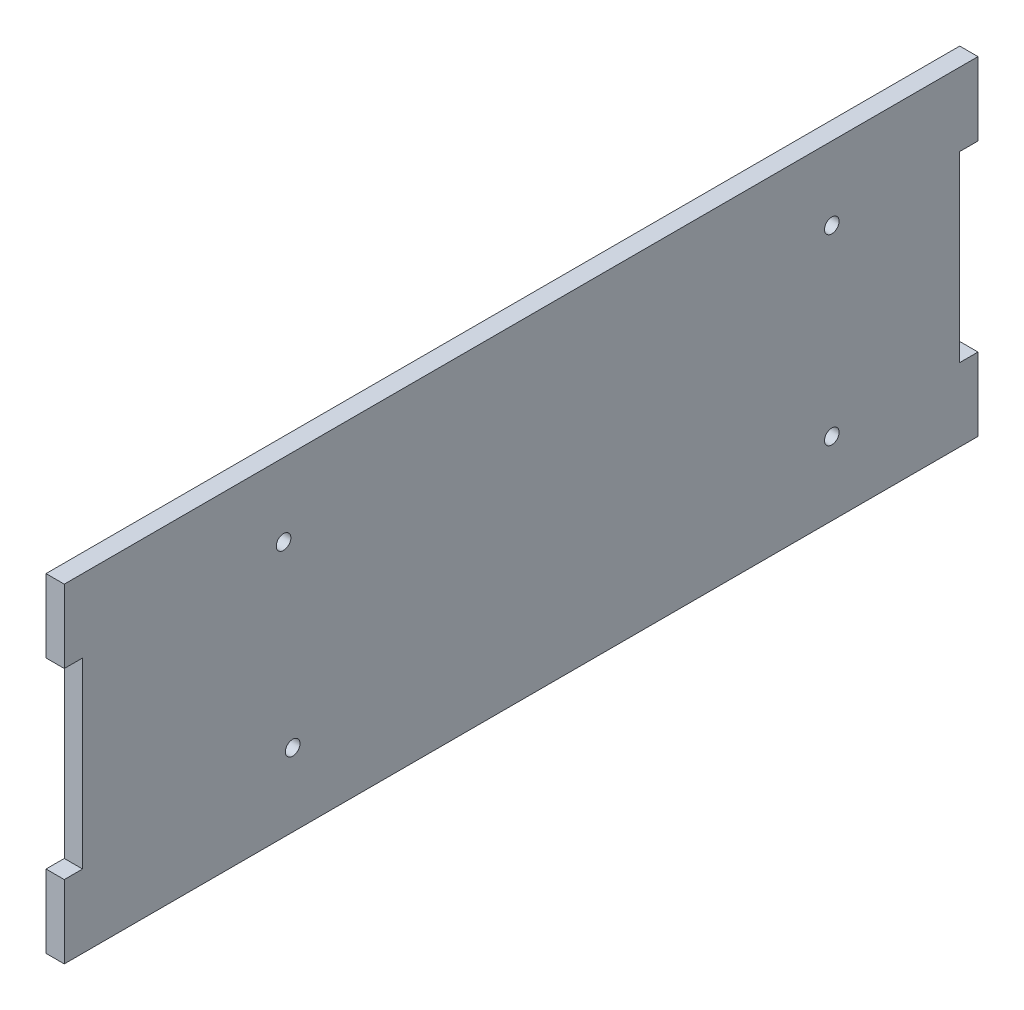
SolidWorks part; units mm, degrees
ref_plane "前视基准面" through (0, 0, 0) normal (0, 0, 1) x (1, 0, 0)
ref_plane "上视基准面" through (0, 0, 0) normal (0, 1, 0) x (1, 0, 0)
ref_plane "右视基准面" through (0, 0, 0) normal (1, 0, 0) x (0, 0, -1)
sketch "草图1" plane through (0, 0, 0) normal (1, 0, 0) x (0, 0, -1)
  line L0 (-276.0239, 70) -> (97.6962, 70) construction
  line L1 (0, 0) -> (-250, 0)
  line L2 (0, 0) -> (0, 20)
  line L3 (0, 90) -> (-250, 90)
  line L4 (-250, 0) -> (-250, 20)
  line L5 (-281.9966, 20) -> (107.0819, 20) construction
  line L6 (-190, 207.5512) -> (-190, -63.3532) construction
  line L7 (-40, 207.5512) -> (-40, -60.3669) construction
  line L8 (-245, 70) -> (-245, 20)
  line L10 (-250, 70) -> (-245, 70)
  line L11 (-250, 20) -> (-245, 20)
  line L12 (0, 20) -> (-5, 20)
  line L13 (0, 70) -> (-5, 70)
  line L14 (-250, 70) -> (-250, 90)
  line L15 (0, 70) -> (0, 90)
  line L16 (-5, 70) -> (-5, 20)
  circle A0 centre (-40, 70) radius 2
  circle A1 centre (-40, 20) radius 2
  circle A2 centre (-187.5, 20) radius 2
  circle A3 centre (-190, 70) radius 2
  dimension "D7" = 5
  dimension "D1" = 250
  dimension "D2" = 90
  dimension "D3" = 50
  dimension "D4" = 150
  dimension "D5" = 40
  dimension "D6" = 20
  dimension "D8" = 20
  dimension "D9" = 20
  dimension "D10" = 50
extrude "凸台-拉伸1" add sketch "草图1" along normal blind 5
